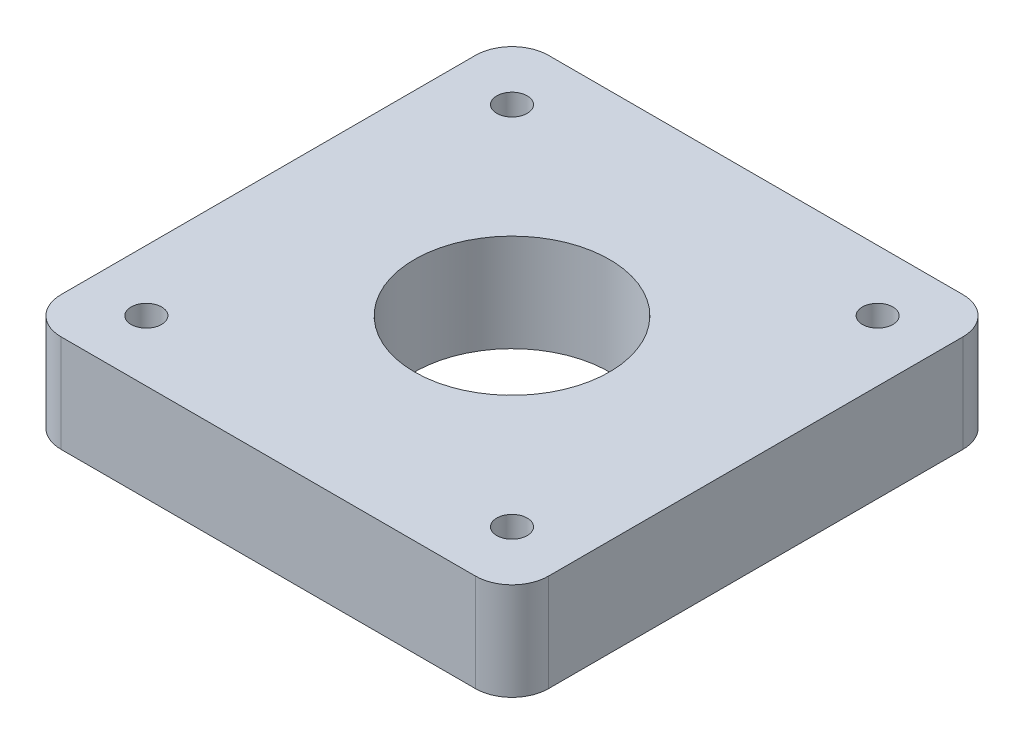
SolidWorks part; units mm, degrees
material "Oak"
ref_plane "Front Plane" through (0, 0, 0) normal (0, 0, 1) x (1, 0, 0)
ref_plane "Top Plane" through (0, 0, 0) normal (0, 1, 0) x (1, 0, 0)
ref_plane "Right Plane" through (0, 0, 0) normal (1, 0, 0) x (0, 0, -1)
sketch "Sketch1" plane through (0, 0, 0) normal (0, 1, 0) x (1, 0, 0)
  line L1 (0, 0.1114) -> (40, 0.1114)
  line L2 (0, 0.1114) -> (0, -39.8886)
  line L3 (0, -39.8886) -> (40, -39.8886)
  line L4 (40, 0.1114) -> (40, -39.8886)
  circle A0 centre (20, -19.8886) radius 8
  dimension "D5" = 16
  dimension "D1" = 40
  dimension "D2" = 40
  dimension "D3" = 20
  dimension "D4" = 20
extrude "Boss-Extrude1" add sketch "Sketch1" along normal blind 8
sketch "Sketch12" plane through (0, 8, 0) normal (0, 1, 0) x (1, 0, 0)
  line L0 (40, 0.1114) -> (0, 0.1114) construction
  line L1 (0, 0.1114) -> (0, -39.8886) construction
  line L2 (40, -39.8886) -> (40, 0.1114) construction
  line L3 (0, -39.8886) -> (40, -39.8886) construction
  circle A0 centre (5, -4.8886) radius 1.25
  circle A1 centre (35, -4.8886) radius 1.25
  circle A2 centre (35, -34.8886) radius 1.25
  circle A3 centre (5, -34.8886) radius 1.25
  dimension "D1" = 2.5
  dimension "D2" = 2.5
  dimension "D3" = 2.5
  dimension "D4" = 2.5
  dimension "D5" = 5
  dimension "D6" = 5
  dimension "D7" = 5
  dimension "D8" = 5
  dimension "D9" = 5
  dimension "D10" = 5
  dimension "D11" = 5
  dimension "D12" = 5
extrude "Cut-Extrude1" cut sketch "Sketch12" against normal through all
fillet "Fillet1" radius 3 4 edges at (40, 4, 39.8886) (40, 4, -0.1114) (0, 4, -0.1114) (0, 4, 39.8886)
